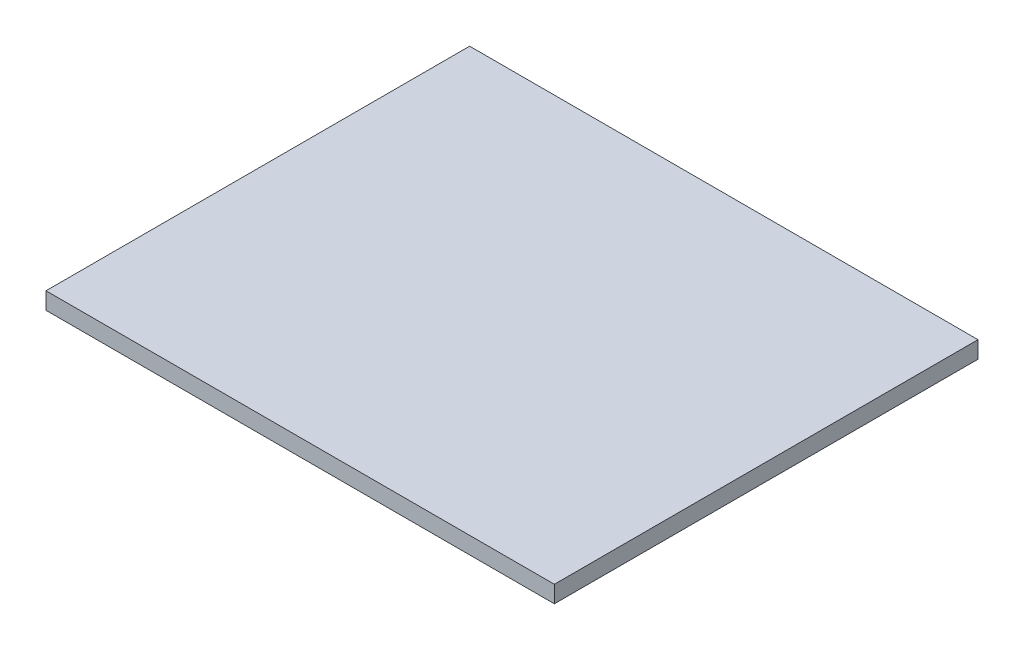
SolidWorks part; units mm, degrees
material "1023 Tôle d'acier au carbone (SS)"
ref_plane "Plan de face" through (0, 0, 0) normal (0, 0, 1) x (1, 0, 0)
ref_plane "Plan de dessus" through (0, 0, 0) normal (0, 1, 0) x (1, 0, 0)
ref_plane "Plan de droite" through (0, 0, 0) normal (1, 0, 0) x (0, 0, -1)
sketch "Esquisse1" plane through (0, 0, 0) normal (0, 1, 0) x (1, 0, 0)
  line L1 (-600, -500) -> (600, -500)
  line L2 (-600, -500) -> (-600, 500)
  line L3 (-600, 500) -> (600, 500)
  line L4 (600, -500) -> (600, 500)
  line L5 (-600, -500) -> (600, 500) construction
  line L6 (-600, 500) -> (600, -500) construction
  point P0 (0, 0)
  dimension "D1" = 1200
  dimension "D2" = 1000
extrude "Boss.-Extru.1" add sketch "Esquisse1" against normal blind 40
sketch "Esquisse2" plane through (0, -40, 0) normal (0, -1, 0) x (1, 0, 0)
  line L1 (-125, -125) -> (125, -125)
  line L2 (-125, -125) -> (-125, 125)
  line L3 (-125, 125) -> (125, 125)
  line L4 (125, -125) -> (125, 125)
  line L5 (-125, -125) -> (125, 125) construction
  line L6 (-125, 125) -> (125, -125) construction
  point P0 (0, 0)
  dimension "D1" = 250
  dimension "D2" = 250
extrude "Boss.-Extru.2" add sketch "Esquisse2" along normal blind 100
